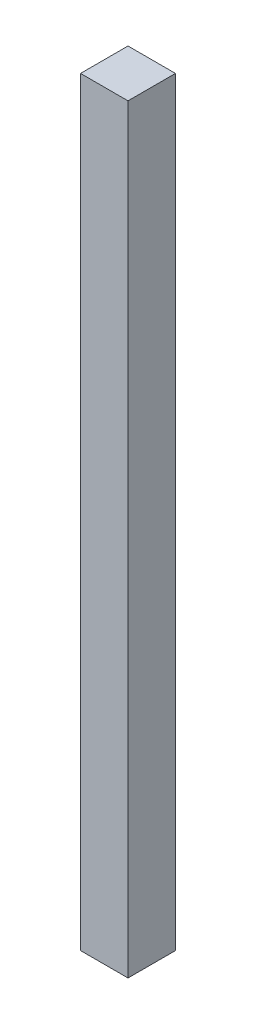
SolidWorks part; units mm, degrees
ref_plane "前视基准面" through (0, 0, 0) normal (0, 0, 1) x (1, 0, 0)
ref_plane "上视基准面" through (0, 0, 0) normal (0, 1, 0) x (1, 0, 0)
ref_plane "右视基准面" through (0, 0, 0) normal (1, 0, 0) x (0, 0, -1)
other "Configuration Table"
sketch "草图1" plane through (0, 0, 0) normal (0, 1, 0) x (1, 0, 0)
  line L1 (0, 0) -> (2.5, 0)
  line L2 (0, 0) -> (0, -2.5)
  line L3 (0, -2.5) -> (2.5, -2.5)
  line L4 (2.5, 0) -> (2.5, -2.5)
extrude "凸台-拉伸1" add sketch "草图1" along normal blind 40
